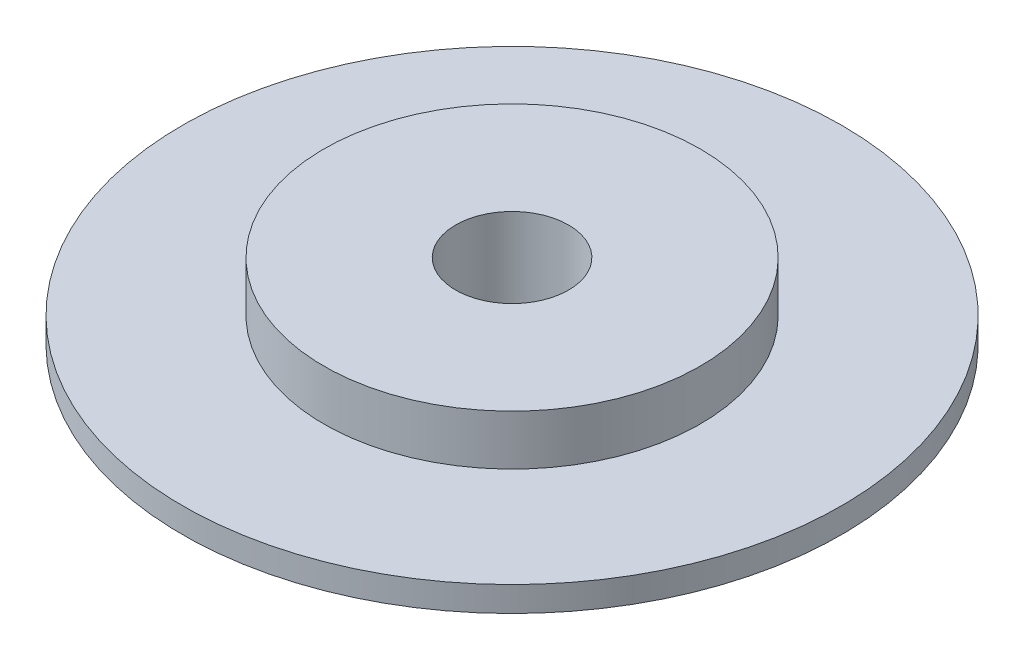
SolidWorks part; units mm, degrees
ref_plane "Front Plane" through (0, 0, 0) normal (0, 0, 1) x (1, 0, 0)
ref_plane "Top Plane" through (0, 0, 0) normal (0, 1, 0) x (1, 0, 0)
ref_plane "Right Plane" through (0, 0, 0) normal (1, 0, 0) x (0, 0, -1)
sketch "Sketch1" plane through (0, 0, 0) normal (0, 0, 1) x (1, 0, 0)
  line L0 (-2.25, 1.7734) -> (-2.25, 6.7734)
  line L13 (-2.25, 6.7734) -> (-7.5, 6.7734)
  line L14 (-7.5, 6.7734) -> (-7.5, 4.7734)
  line L15 (-7.5, 4.7734) -> (-13.1355, 4.7734)
  line L16 (-13.1355, 4.7734) -> (-13.1355, 3.7734)
  line L17 (-13.1355, 3.7734) -> (-7.5, 3.7734)
  line L18 (-7.5, 3.7734) -> (-7.5, 1.7734)
  line L19 (-7.5, 1.7734) -> (-2.25, 1.7734)
  line L20 (0, 0) -> (0, 11.906) construction
  dimension "D1" = 2.25
  dimension "D2" = 7.5
  dimension "D3" = 1
  dimension "D4" = 2
revolve "Revolve1" add sketch "Sketch1" angle 360 about L20
